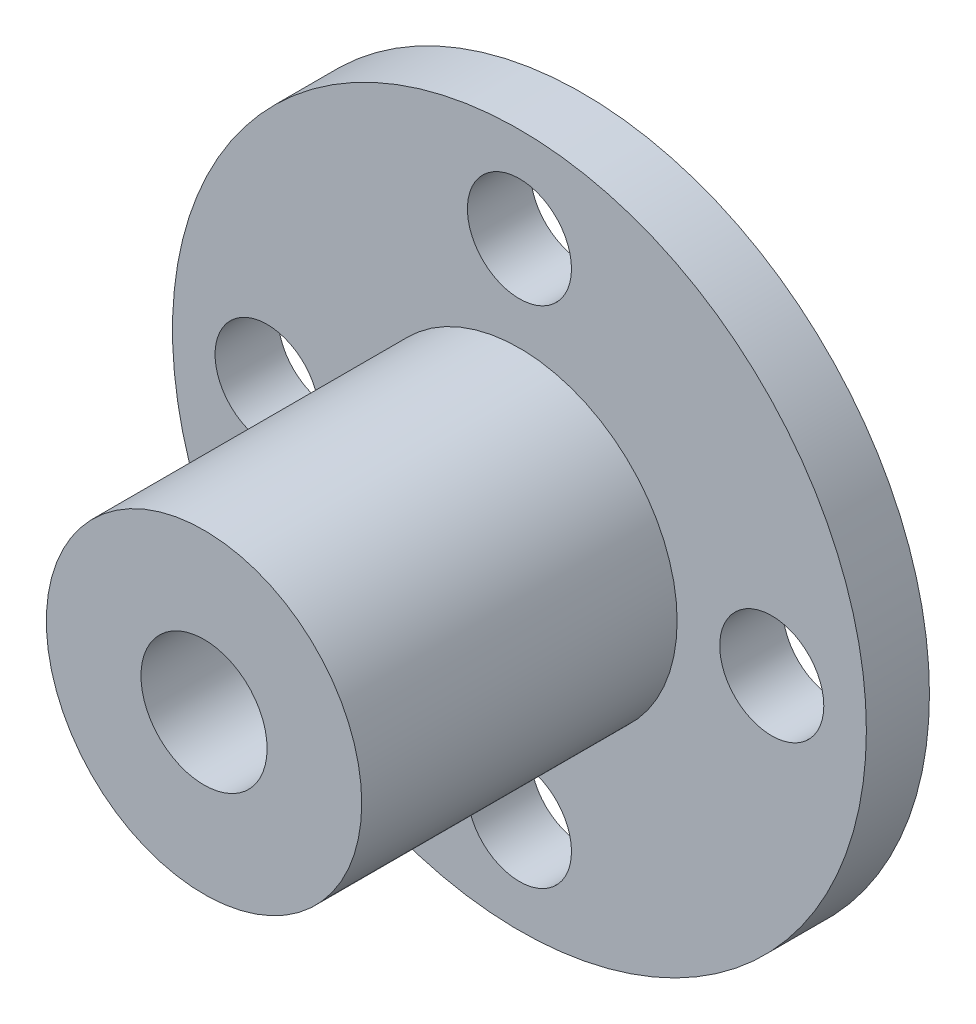
SolidWorks part; units mm, degrees
ref_plane "前视基准面" through (0, 0, 0) normal (0, 0, 1) x (1, 0, 0)
ref_plane "上视基准面" through (0, 0, 0) normal (0, 1, 0) x (1, 0, 0)
ref_plane "右视基准面" through (0, 0, 0) normal (1, 0, 0) x (0, 0, -1)
sketch "草图1" plane through (0, 0, 0) normal (0, 0, 1) x (1, 0, 0)
  circle A0 centre (0, 0) radius 8
  circle A1 centre (0, 0) radius 2
  circle A2 centre (0, 0) radius 11
  circle A3 centre (-8, 0) radius 1.65
  circle A4 centre (0, 8) radius 1.65
  circle A5 centre (8, 0) radius 1.65
  circle A6 centre (0, -8) radius 1.65
  circle A7 centre (0, 0) radius 5
extrude "凸台-拉伸1" add sketch "草图1" along normal blind 2 contours A2 A6 A0 A3 A4 A5 | A6 A0 A5 A4 A3 A7 | A7 A1
sketch "草图2" plane through (0, 0, 2) normal (0, 0, 1) x (1, 0, 0)
  circle A0 centre (0, 0) radius 5
  circle A1 centre (0, 0) radius 2
extrude "凸台-拉伸2" add sketch "草图2" along normal blind 10
